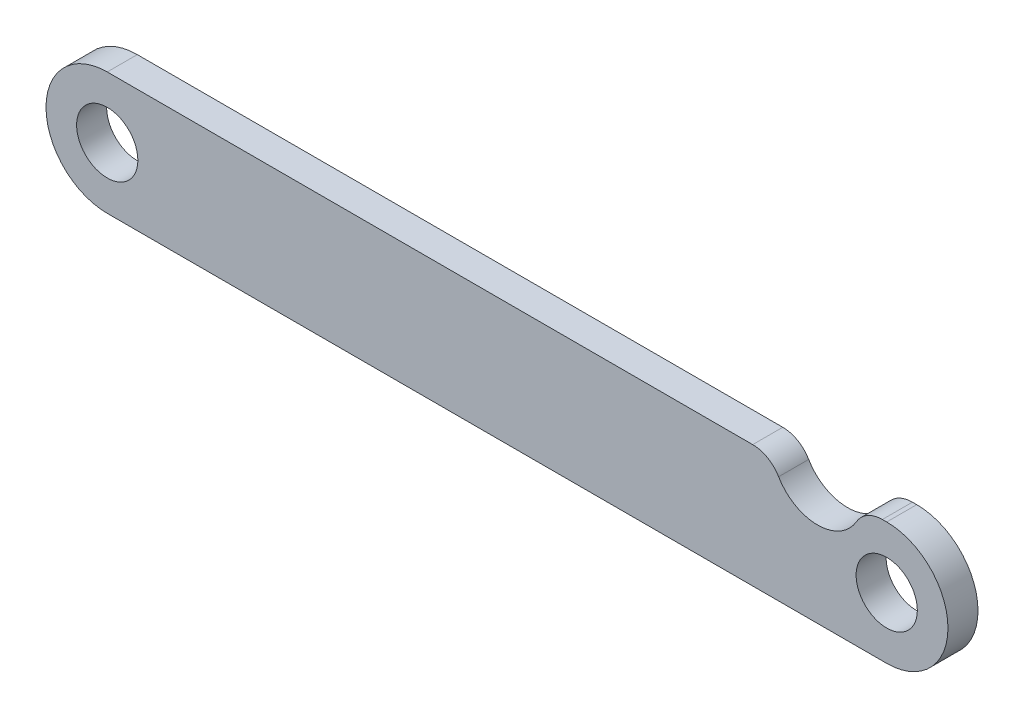
SolidWorks part; units mm, degrees
ref_plane "Спереди" through (0, 0, 0) normal (0, 0, 1) x (1, 0, 0)
ref_plane "Сверху" through (0, 0, 0) normal (0, 1, 0) x (1, 0, 0)
ref_plane "Справа" through (0, 0, 0) normal (1, 0, 0) x (0, 0, -1)
sketch "Sketch1" plane through (0, 0, 0) normal (0, 0, 1) x (1, 0, 0)
  line L0 (0, 0) -> (-25.9411, 0)
  line L1 (-25.9411, 2.038) -> (0, 2.038)
  line L2 (-25.9411, -2.038) -> (0, -2.038)
  circle A0 centre (0, 0) radius 1.019
  circle A1 centre (0, 0) radius 2.038
  circle A2 centre (-25.9411, 0) radius 1.019
  circle A3 centre (-25.9411, 0) radius 2.038
  dimension "D1" = 25.9411
extrude "Extrude1" add sketch "Sketch1" along normal blind 1
sketch "Sketch2" plane through (0, 0, 0) normal (0, 0, 1) x (1, 0, 0)
  circle A1 centre (-2.3022, 2.3) radius 1.5
  dimension "D3" = 3
  dimension "D1" = 2.3022
  dimension "D2" = 2.3
extrude "Cut-Extrude2" cut sketch "Sketch2" along normal through all
fillet "Fillet1" radius 1 2 edges at (-3.7791, 2.038, 0.5) (-0.8252, 2.038, 0.5)
